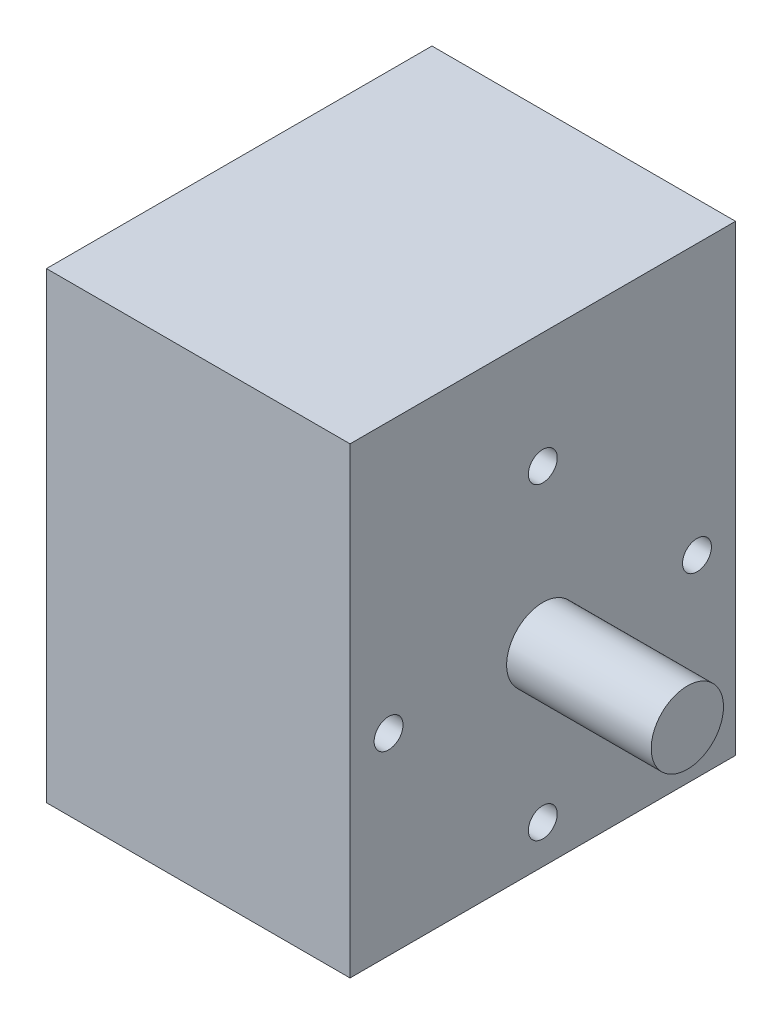
SolidWorks part; units mm, degrees
ref_plane "Front Plane" through (0, 0, 0) normal (0, 0, 1) x (1, 0, 0)
ref_plane "Top Plane" through (0, 0, 0) normal (0, 1, 0) x (1, 0, 0)
ref_plane "Right Plane" through (0, 0, 0) normal (1, 0, 0) x (0, 0, -1)
sketch "Sketch1" plane through (0, 0, 0) normal (1, 0, 0) x (0, 0, -1)
  line L0 (0, 0) -> (0, -40) construction
  line L1 (-40, 56) -> (40, 56)
  line L2 (-40, 56) -> (-40, -40)
  line L3 (-40, -40) -> (40, -40)
  line L4 (40, 56) -> (40, -40)
  circle A0 centre (0, 0) radius 32 construction
  circle A1 centre (0, 32) radius 3
  circle A2 centre (-32, 0) radius 3
  circle A3 centre (0, -32) radius 3
  circle A4 centre (32, 0) radius 3
  dimension "D1" = 64
  dimension "D2" = 6
  dimension "D3" = 80
  dimension "D4" = 8
  dimension "D5" = 24
extrude "Boss-Extrude1" add sketch "Sketch1" against normal blind 63
sketch "Sketch2" plane through (0, 0, 0) normal (1, 0, 0) x (0, 0, -1)
  circle A0 centre (0, 0) radius 7.5
  dimension "D1" = 15
extrude "Boss-Extrude2" add sketch "Sketch2" along normal blind 30
